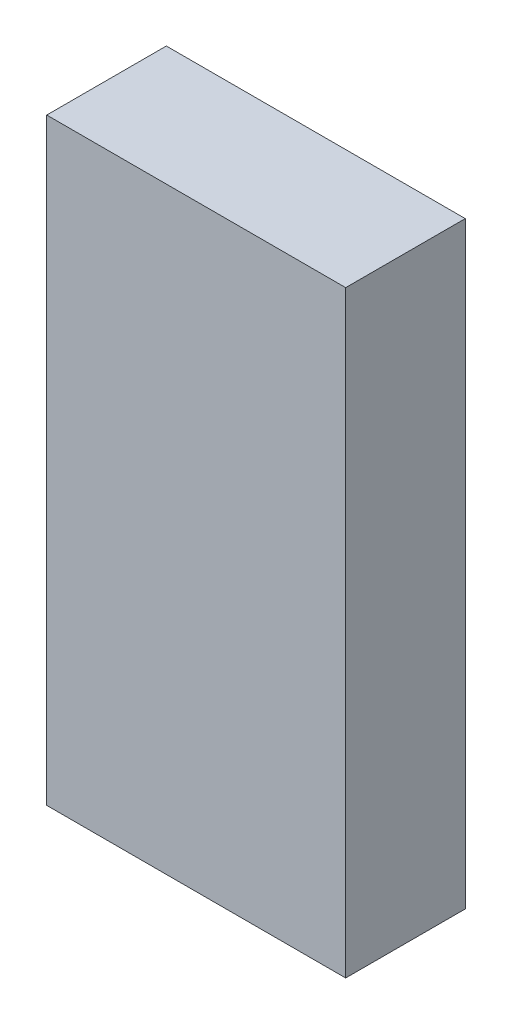
SolidWorks part; units mm, degrees
material "1060 Alloy"
ref_plane "Front Plane" through (0, 0, 0) normal (0, 0, 1) x (1, 0, 0)
ref_plane "Top Plane" through (0, 0, 0) normal (0, 1, 0) x (1, 0, 0)
ref_plane "Right Plane" through (0, 0, 0) normal (1, 0, 0) x (0, 0, -1)
sketch "BaseDrawing" plane through (0, 0, 0) normal (0, 1, 0) x (1, 0, 0)
  line L1 (-25, -10) -> (25, -10)
  line L2 (-25, -10) -> (-25, 10)
  line L3 (-25, 10) -> (25, 10)
  line L4 (25, -10) -> (25, 10)
  line L5 (-25, -10) -> (25, 10) construction
  line L6 (-25, 10) -> (25, -10) construction
  point P0 (0, 0)
  dimension "Length" = 50
  dimension "Depth" = 20
extrude "BaseThickness" add sketch "BaseDrawing" along normal blind 100
